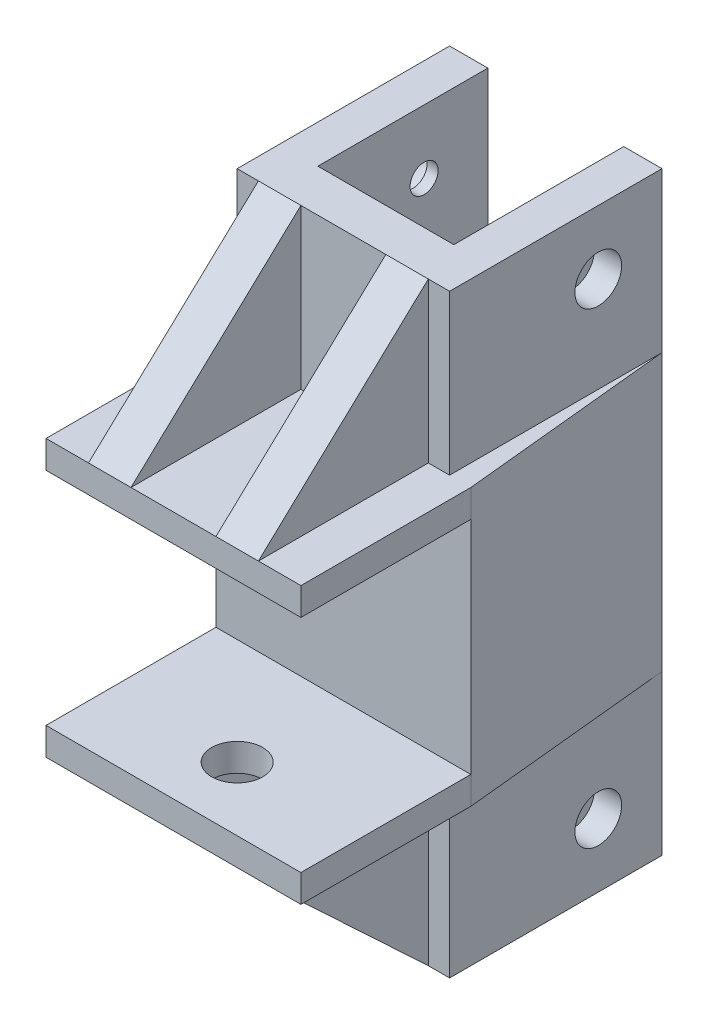
SolidWorks part; units mm, degrees
ref_plane "Front Plane" through (0, 0, 0) normal (0, 0, 1) x (1, 0, 0)
ref_plane "Top Plane" through (0, 0, 0) normal (0, 1, 0) x (1, 0, 0)
ref_plane "Right Plane" through (0, 0, 0) normal (1, 0, 0) x (0, 0, -1)
sketch "Sketch1" plane through (0, 0, 0) normal (1, 0, 0) x (0, 0, -1)
  line L1 (-20, -32.5) -> (20, -32.5)
  line L2 (-20, -32.5) -> (-20, 32.5)
  line L3 (-20, 32.5) -> (20, 32.5)
  line L4 (20, -32.5) -> (20, 32.5)
  line L5 (-20, -32.5) -> (20, 32.5) construction
  line L6 (-20, 32.5) -> (20, -32.5) construction
  point P0 (0, 0)
  dimension "D1" = 65
  dimension "D2" = 40
extrude "Boss-Extrude1" add sketch "Sketch1" along normal mid plane 60
sketch "Sketch2" plane through (0, 0, 0) normal (1, 0, 0) x (0, 0, -1)
  line L0 (-20, 32.5) -> (-20, -32.5) construction
  line L1 (-20, 26) -> (20, 26)
  line L2 (-20, 26) -> (-20, -26)
  line L3 (-20, -26) -> (20, -26)
  line L4 (20, 26) -> (20, -26)
  line L5 (0, 0) -> (20, 0) construction
  dimension "D1" = 52
  dimension "D2" = 40
extrude "Cut-Extrude1" cut sketch "Sketch2" against normal through all both and the other way through all
sketch "Sketch3" plane through (0, 0, 0) normal (0, 1, 0) x (1, 0, 0)
  line L0 (0, 0) -> (0, -20) construction
  line L1 (30, -20) -> (-30, -20) construction
  circle A0 centre (0, -5) radius 6
  dimension "D1" = 12
  dimension "D2" = 15
extrude "Cut-Extrude2" cut sketch "Sketch3" against normal up to surface (32.5 mm away) up to face at (0, -32.5, 0)
sketch "Sketch4" plane through (0, 0, -20) normal (0, 0, -1) x (-1, 0, 0)
  line L1 (-25, -70) -> (25, -70)
  line L2 (-25, -70) -> (-25, 70)
  line L3 (-25, 70) -> (25, 70)
  line L4 (25, -70) -> (25, 70)
  line L5 (-25, -70) -> (25, 70) construction
  line L6 (-25, 70) -> (25, -70) construction
  point P0 (0, 0)
  dimension "D1" = 50
  dimension "D2" = 140
extrude "Boss-Extrude2" add sketch "Sketch4" along normal blind 50
sketch "Sketch8" plane through (0, 0, 0) normal (1, 0, 0) x (0, 0, -1)
  line L0 (20, 70) -> (-20, 32.5)
  line L1 (20, 32.5) -> (-20, 32.5) construction
  line L2 (-20, 32.5) -> (20, 32.5)
  line L3 (20, 32.5) -> (20, 70)
  line L4 (0, 0) -> (65.7965, 0) construction
  line L6 (20, -32.5) -> (20, -70)
  line L7 (-20, -32.5) -> (20, -32.5)
  line L8 (20, -70) -> (-20, -32.5)
extrude "Boss-Extrude3" add sketch "Sketch8" along normal mid plane 40
sketch "Sketch9" plane through (0, 0, 0) normal (1, 0, 0) x (0, 0, -1)
  line L3 (20, 70) -> (-20, 32.5)
  line L4 (-20, 32.5) -> (20, 32.5)
  line L5 (20, 32.5) -> (20, 70)
  line L6 (20, 70) -> (-20, 32.5)
  line L7 (-20, 32.5) -> (20, 32.5)
  line L8 (20, 32.5) -> (20, 70)
  line L9 (-20, -32.5) -> (20, -70)
  line L10 (20, -70) -> (20, -32.5)
  line L11 (20, -32.5) -> (-20, -32.5)
  line L12 (-20, -32.5) -> (20, -70)
  line L13 (20, -70) -> (20, -32.5)
  line L14 (20, -32.5) -> (-20, -32.5)
  dimension "D1" = 0
  dimension "D2" = 0
extrude "Cut-Extrude3" cut sketch "Sketch9" against normal mid plane 20
sketch "Sketch10" plane through (0, 0, 0) normal (0, 1, 0) x (1, 0, 0)
  line L0 (0, 0) -> (0, 70) construction
  line L1 (-25, 70) -> (25, 70) construction
  line L3 (-16, 70) -> (16, 70)
  line L4 (-16, 70) -> (-16, 30)
  line L5 (-16, 30) -> (16, 30)
  line L6 (16, 70) -> (16, 30)
  dimension "D1" = 40
  dimension "D2" = 32
extrude "Cut-Extrude4" cut sketch "Sketch10" against normal through all both and the other way through all
sketch "Sketch11" plane through (0, 0, 0) normal (1, 0, 0) x (0, 0, -1)
  line L0 (0, 0) -> (70, 0) construction
  line L1 (70, 70) -> (70, -70) construction
  line L2 (70, 70) -> (20, 70) construction
  circle A0 centre (55, 55) radius 3.3
  circle A1 centre (55, -55) radius 3.3
  point P13 (50, 55)
  dimension "D1" = 6.6
  dimension "D2" = 15
  dimension "D3" = 15
extrude "Cut-Extrude5" cut sketch "Sketch11" against normal through all both and the other way through all
sketch "Sketch12" plane through (25, 0, 0) normal (1, 0, 0) x (0, 0, -1)
  circle A0 centre (55, 55) radius 5.5
  circle A1 centre (55, -55) radius 5.5
  dimension "D1" = 11
extrude "Cut-Extrude6" cut sketch "Sketch12" against normal blind 6.4 and the other way through all
mirror "Mirror1" about plane through (0, 0, 0) normal (1, 0, 0) of "Cut-Extrude6"
sketch "Sketch13" plane through (0, 26, 0) normal (0, 1, 0) x (1, 0, 0)
  circle A0 centre (0, -5) radius 6
  circle A2 centre (0, -5) radius 6 construction
extrude "Cut-Extrude7" cut sketch "Sketch13" along normal blind 3
sketch "Sketch15" plane through (0, 0, 0) normal (0, 1, 0) x (1, 0, 0)
  line L0 (30, 20) -> (25, 70)
  line L1 (25, 70) -> (25, 20)
  line L2 (25, 20) -> (30, 20)
  line L3 (0, 0) -> (0, 50.4689) construction
  line L4 (-25, 20) -> (-30, 20)
  line L5 (-25, 70) -> (-25, 20)
  line L6 (-30, 20) -> (-25, 70)
extrude "Boss-Extrude4" add sketch "Sketch15" along normal up to surface and the other way up to surface
